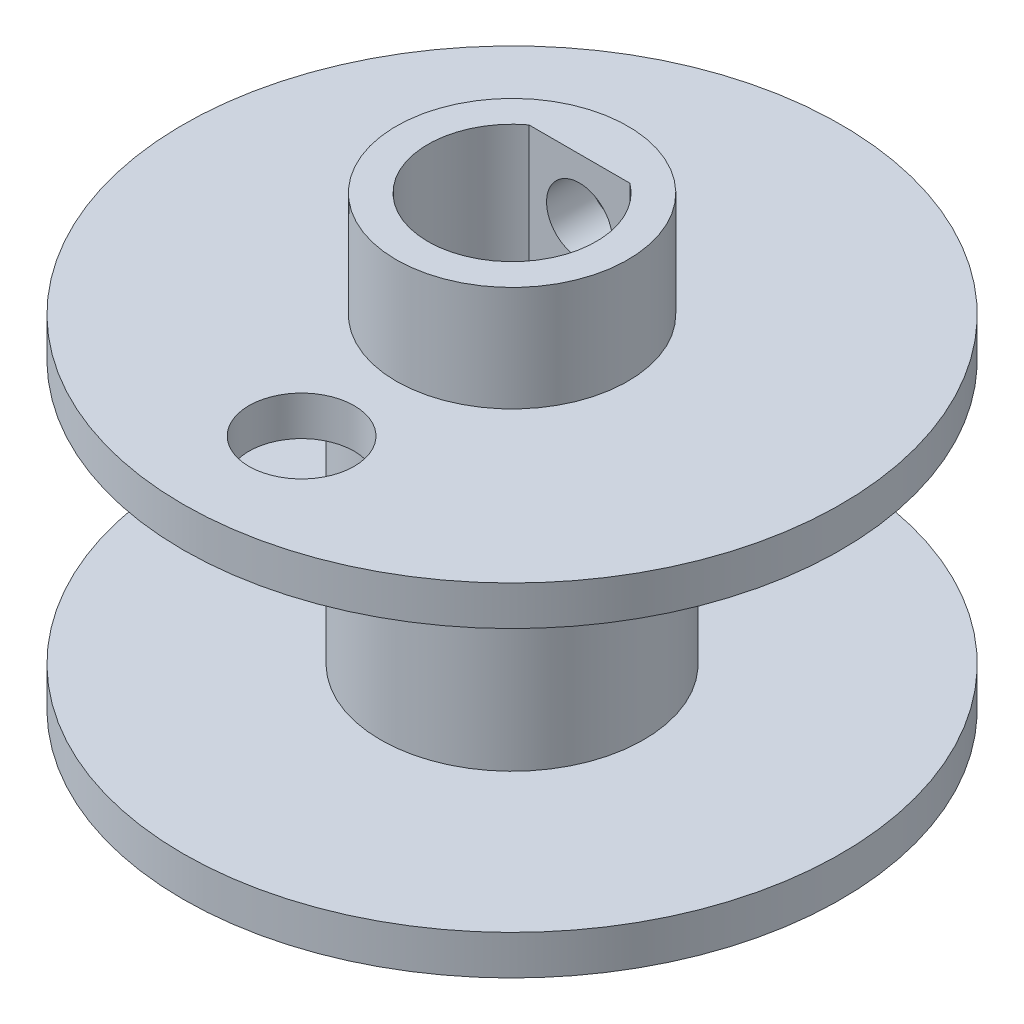
SolidWorks part; units mm, degrees
ref_plane "Front Plane" through (0, 0, 0) normal (0, 0, 1) x (1, 0, 0)
ref_plane "Top Plane" through (0, 0, 0) normal (0, 1, 0) x (1, 0, 0)
ref_plane "Right Plane" through (0, 0, 0) normal (1, 0, 0) x (0, 0, -1)
sketch "Sketch2" plane through (0, 0, 0) normal (0, 1, 0) x (1, 0, 0)
  circle A0 centre (0, 0) radius 5
  dimension "D1" = 10
extrude "Boss-Extrude1" add sketch "Sketch2" along normal mid plane 10
sketch "Sketch3" plane through (0, 5, 0) normal (0, 1, 0) x (1, 0, 0)
  circle A0 centre (0, 0) radius 12.5
  dimension "D1" = 25
extrude "Boss-Extrude2" add sketch "Sketch3" along normal blind 1.5
mirror "Mirror1" about plane through (0, 0, 0) normal (0, 1, 0) of "Boss-Extrude2"
sketch "Sketch4" plane through (0, 6.5, 0) normal (0, 1, 0) x (1, 0, 0)
  line L0 (-1.92, 2.56) -> (1.92, 2.56)
  line L1 (-55, 0) -> (55, 0) construction
  arc A0 (-1.92, 2.56) -> (1.92, 2.56) centre (0, 0) ccw
  dimension "D1" = 6.4
  dimension "D2" = 3.84
extrude "Cut-Extrude1" cut sketch "Sketch4" against normal through all and the other way through all
sketch "Sketch5" plane through (0, 6.5, 0) normal (0, 1, 0) x (1, 0, 0)
  circle A0 centre (0, 0) radius 4.4
  dimension "D1" = 8.8
extrude "Boss-Extrude3" add sketch "Sketch5" along normal blind 4
sketch "Sketch6" plane through (0, 10.5, 0) normal (0, 1, 0) x (1, 0, 0)
  line L0 (-1.92, 2.56) -> (1.92, 2.56)
  line L1 (-55, 0) -> (55, 0) construction
  arc A0 (-1.92, 2.56) -> (1.92, 2.56) centre (0, 0) ccw
  dimension "D1" = 6.4
  dimension "D2" = 3.84
extrude "Cut-Extrude2" cut sketch "Sketch6" against normal through all
sketch "Sketch7" plane through (0, 0, -2.56) normal (0, 0, 1) x (1, 0, 0)
  line L0 (1.92, 10.5) -> (-1.92, 10.5) construction
  circle A0 centre (0, 8.3) radius 1.25
  dimension "D1" = 2.5
  dimension "D2" = 2.2
extrude "Cut-Extrude3" cut sketch "Sketch7" against normal through all
sketch "Sketch9" plane through (0, 5, 0) normal (0, -1, 0) x (1, 0, 0)
  line L0 (0, -9.35) -> (0, 9.35) construction
  line L1 (9.35, 0) -> (-9.35, 0) construction
  circle A0 centre (0, 8) radius 2
  dimension "D1" = 4
  dimension "D2" = 0
  dimension "D3" = 8
extrude "Cut-Extrude4" cut sketch "Sketch9" against normal through all
